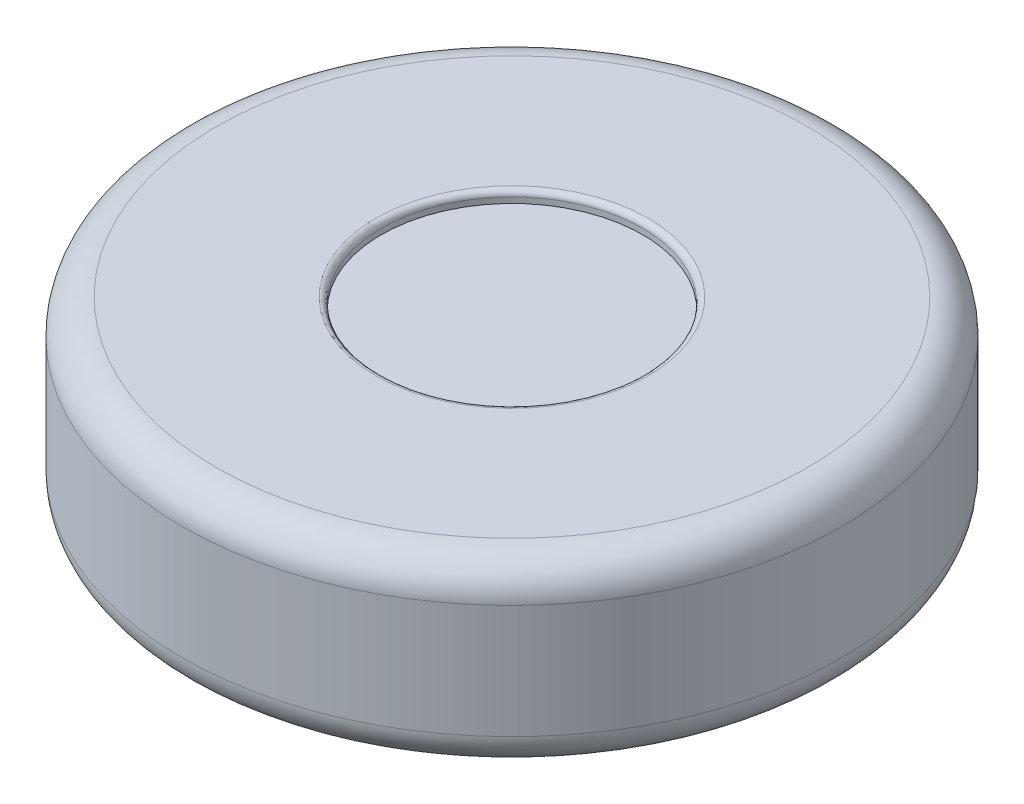
SolidWorks part; units mm, degrees
ref_plane "Alzado" through (0, 0, 0) normal (0, 0, 1) x (1, 0, 0)
ref_plane "Planta" through (0, 0, 0) normal (0, 1, 0) x (1, 0, 0)
ref_plane "Vista lateral" through (0, 0, 0) normal (1, 0, 0) x (0, 0, -1)
sketch "Croquis1" plane through (0, 0, 0) normal (0, 1, 0) x (1, 0, 0)
  circle A0 centre (0, 0) radius 115
  dimension "D1" = 230
extrude "Saliente-Extruir1" add sketch "Croquis1" along normal blind 140
ref_plane "Plano1" through (0, 70, 0) normal (0, 1, 0) x (1, 0, 0)
sketch "Croquis2" plane through (0, 70, 0) normal (0, 1, 0) x (1, 0, 0)
  circle A0 centre (0, 0) radius 115
  circle A1 centre (0, 0) radius 290
  dimension "D1" = 230
  dimension "D2" = 580
extrude "Saliente-Extruir2" add sketch "Croquis2" along normal blind 80 and the other way blind 80
fillet "Redondeo1" radius 30 2 edges at (0, 150, 290) (0, -10, 290)
fillet "Redondeo2" radius 5 1 edges at (0, -10, 115)
fillet "Redondeo3" radius 5 1 edges at (0, 150, 115)
